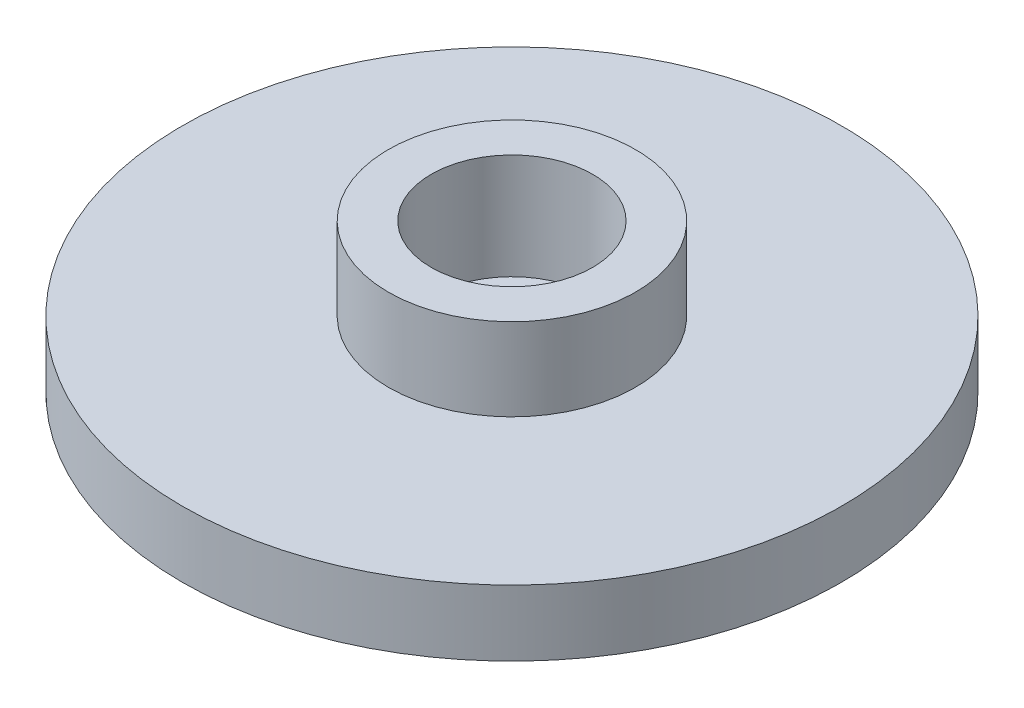
SolidWorks part; units mm, degrees
material "AISI 304"
ref_plane "前视基准面" through (0, 0, 0) normal (0, 0, 1) x (1, 0, 0)
ref_plane "上视基准面" through (0, 0, 0) normal (0, 1, 0) x (1, 0, 0)
ref_plane "右视基准面" through (0, 0, 0) normal (1, 0, 0) x (0, 0, -1)
other "Configuration Table"
sketch "草图1" plane through (0, 0, 0) normal (0, 1, 0) x (1, 0, 0)
  circle A0 centre (0, 0) radius 1.25
  circle A1 centre (0, 0) radius 10
  dimension "D1" = 2.5
  dimension "D2" = 20
extrude "凸台-拉伸1" add sketch "草图1" along normal blind 2
sketch "草图2" plane through (0, 2, 0) normal (0, 1, 0) x (1, 0, 0)
  circle A0 centre (0, 0) radius 3.75
  dimension "D1" = 7.5
extrude "凸台-拉伸2" add sketch "草图2" along normal blind 2.5
sketch "草图4" plane through (0, 4.5, 0) normal (0, 1, 0) x (1, 0, 0)
  circle A0 centre (0, 0) radius 2.45
  dimension "D1" = 4.9
extrude "切除-拉伸1" cut sketch "草图4" against normal blind 3.2
